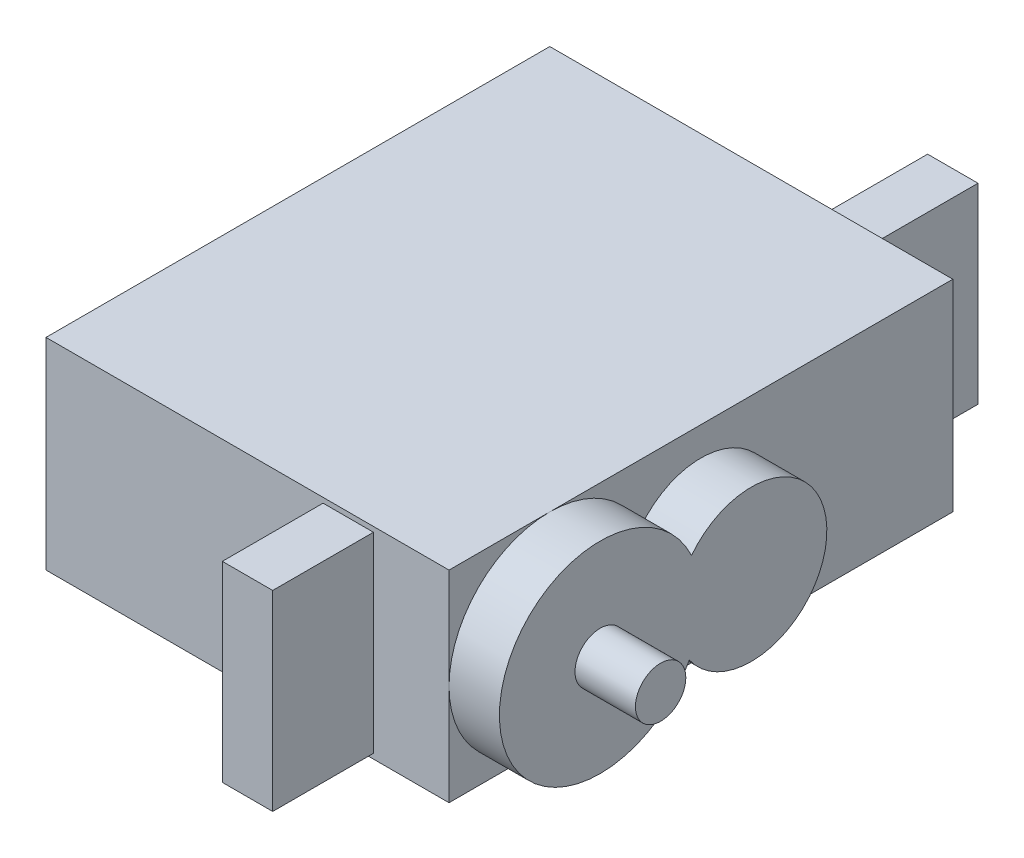
SolidWorks part; units mm, degrees
ref_plane "Front Plane" through (0, 0, 0) normal (0, 0, 1) x (1, 0, 0)
ref_plane "Top Plane" through (0, 0, 0) normal (0, 1, 0) x (1, 0, 0)
ref_plane "Right Plane" through (0, 0, 0) normal (1, 0, 0) x (0, 0, -1)
sketch "Sketch1" plane through (0, 0, 0) normal (0, 1, 0) x (1, 0, 0)
  line L1 (-10, -12.5) -> (10, -12.5)
  line L2 (-10, -12.5) -> (-10, 12.5)
  line L3 (-10, 12.5) -> (10, 12.5)
  line L4 (10, -12.5) -> (10, 12.5)
  line L5 (-10, -12.5) -> (10, 12.5) construction
  line L6 (-10, 12.5) -> (10, -12.5) construction
  point P0 (0, 0)
  dimension "D1" = 20
  dimension "D2" = 25
extrude "Boss-Extrude1" add sketch "Sketch1" along normal blind 10
sketch "Sketch3" plane through (0, 0, -12.5) normal (0, 0, -1) x (-1, 0, 0)
  line L0 (-10, 5) -> (-5, 5) construction
  line L1 (-10, 10) -> (-10, 0) construction
  line L3 (-6.25, 0.25) -> (-3.75, 0.25)
  line L4 (-6.25, 0.25) -> (-6.25, 9.75)
  line L5 (-6.25, 9.75) -> (-3.75, 9.75)
  line L6 (-3.75, 0.25) -> (-3.75, 9.75)
  line L7 (-6.25, 0.25) -> (-3.75, 9.75) construction
  line L8 (-6.25, 9.75) -> (-3.75, 0.25) construction
  dimension "D1" = 5
  dimension "D2" = 9.5
  dimension "D3" = 2.5
extrude "Boss-Extrude3" add sketch "Sketch3" along normal blind 5
sketch "Sketch4" plane through (0, 0, 12.5) normal (0, 0, 1) x (1, 0, 0)
  line L0 (10, 5) -> (5, 5) construction
  line L1 (10, 10) -> (10, 0) construction
  line L3 (3.75, 0.25) -> (6.25, 0.25)
  line L4 (3.75, 0.25) -> (3.75, 9.75)
  line L5 (3.75, 9.75) -> (6.25, 9.75)
  line L6 (6.25, 0.25) -> (6.25, 9.75)
  line L7 (3.75, 0.25) -> (6.25, 9.75) construction
  line L8 (3.75, 9.75) -> (6.25, 0.25) construction
  dimension "D1" = 5
  dimension "D2" = 9.5
  dimension "D3" = 2.5
extrude "Boss-Extrude4" add sketch "Sketch4" along normal blind 5
sketch "Sketch5" plane through (10, 0, 0) normal (1, 0, 0) x (0, 0, -1)
  line L0 (-12.5, 10) -> (-12.5, 0) construction
  line L1 (-12.5, 10) -> (-12.5, 0) construction
  line L2 (-12.5, 5) -> (-7.5, 5) construction
  line L3 (-7.5, 5) -> (0, 5) construction
  arc A0 (-2.9674, 7.1108) -> (-3.0751, 2.6718) centre (-7.5, 5) ccw
  arc A1 (-3.0751, 2.6718) -> (-2.9674, 7.1108) centre (0, 4.818) ccw
  dimension "D3" = 7.5
  dimension "D1" = 5
  dimension "D2" = 7.5
extrude "Boss-Extrude5" add sketch "Sketch5" along normal blind 2.5
sketch "Sketch6" plane through (12.5, 0, 0) normal (1, 0, 0) x (0, 0, -1)
  circle A0 centre (-7.5, 5) radius 1.25
  dimension "D1" = 2.5
extrude "Boss-Extrude6" add sketch "Sketch6" along normal blind 3
